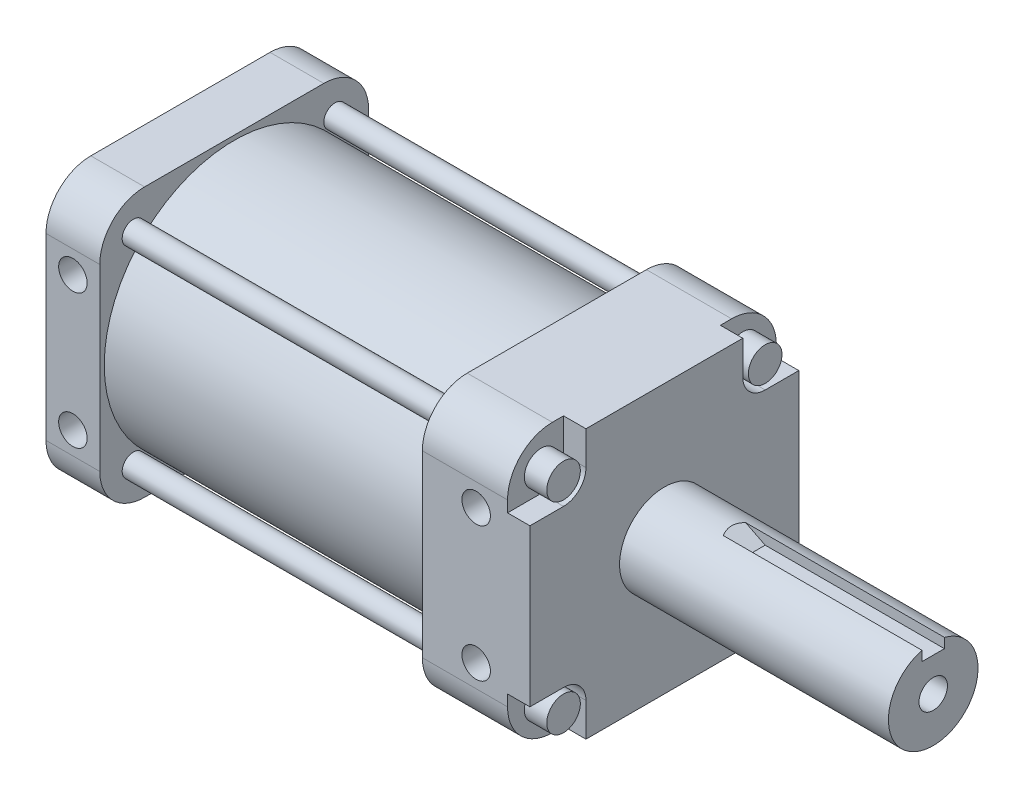
SolidWorks part; units mm, degrees
material "AISI 4130 Steel, normalized at 870C"
ref_plane "Front Plane" through (0, 0, 0) normal (0, 0, 1) x (1, 0, 0)
ref_plane "Top Plane" through (0, 0, 0) normal (0, 1, 0) x (1, 0, 0)
ref_plane "Right Plane" through (0, 0, 0) normal (1, 0, 0) x (0, 0, -1)
sketch "Sketch1" plane through (0, 0, 0) normal (1, 0, 0) x (0, 0, -1)
  line L0 (0, 19.05) -> (0, -19.05) construction
  line L1 (-12.7, 19.05) -> (12.7, 19.05)
  line L2 (-19.05, 12.7) -> (-19.05, -12.7)
  line L3 (-12.7, -19.05) -> (12.7, -19.05)
  line L4 (19.05, 12.7) -> (19.05, -12.7)
  arc A0 (12.7, 19.05) -> (19.05, 12.7) centre (12.7, 12.7) cw
  arc A1 (12.7, -19.05) -> (19.05, -12.7) centre (12.7, -12.7) ccw
  arc A2 (-19.05, -12.7) -> (-12.7, -19.05) centre (-12.7, -12.7) ccw
  arc A3 (-12.7, 19.05) -> (-19.05, 12.7) centre (-12.7, 12.7) ccw
  dimension "D2" = 6.35
  dimension "D1" = 38.1
extrude "Boss-Extrude1" add sketch "Sketch1" along normal blind 7.62
sketch "Sketch2" plane through (7.62, 0, 0) normal (1, 0, 0) x (0, 0, -1)
  circle A0 centre (0, 0) radius 18.415
  dimension "D1" = 36.83
extrude "Boss-Extrude2" add sketch "Sketch2" along normal blind 45.72
sketch "Sketch4" plane through (53.34, 0, 0) normal (1, 0, 0) x (0, 0, -1)
  line L0 (12.7, 19.05) -> (-12.7, 19.05) construction
  line L1 (-19.05, 12.7) -> (-19.05, -12.7) construction
  line L2 (-12.7, -19.05) -> (12.7, -19.05) construction
  line L3 (19.05, -12.7) -> (19.05, 12.7) construction
  line L4 (12.7, 19.05) -> (-12.7, 19.05)
  line L5 (-19.05, 12.7) -> (-19.05, -12.7)
  line L6 (-12.7, -19.05) -> (12.7, -19.05)
  line L7 (19.05, -12.7) -> (19.05, 12.7)
  arc A0 (-12.7, 19.05) -> (-19.05, 12.7) centre (-12.7, 12.7) ccw construction
  arc A1 (-19.05, -12.7) -> (-12.7, -19.05) centre (-12.7, -12.7) ccw construction
  arc A2 (12.7, -19.05) -> (19.05, -12.7) centre (12.7, -12.7) ccw construction
  arc A3 (19.05, 12.7) -> (12.7, 19.05) centre (12.7, 12.7) ccw construction
  arc A4 (-12.7, 19.05) -> (-19.05, 12.7) centre (-12.7, 12.7) ccw
  arc A5 (-19.05, -12.7) -> (-12.7, -19.05) centre (-12.7, -12.7) ccw
  arc A6 (12.7, -19.05) -> (19.05, -12.7) centre (12.7, -12.7) ccw
  arc A7 (19.05, 12.7) -> (12.7, 19.05) centre (12.7, 12.7) ccw
extrude "Boss-Extrude3" add sketch "Sketch4" along normal blind 15.24
sketch "Sketch5" plane through (68.58, 0, 0) normal (1, 0, 0) x (0, 0, -1)
  circle A0 centre (0, 0) radius 6.35
  dimension "D1" = 12.7
extrude "Boss-Extrude4" add sketch "Sketch5" along normal blind 38.1
hole_wizard "#10-32 Tapped Hole1" positions "3DSketch1" profile "Sketch6" tap size "#10-32" standard "ANSI Inch"
sketch3d "3DSketch1"
  line L18 (68.58, 0, -19.05) -> (53.34, 0, -19.05) construction
  line L19 (68.58, -12.7, -19.05) -> (68.58, 12.7, -19.05) construction
  line L20 (53.34, -12.7, -19.05) -> (53.34, 12.7, -19.05) construction
  line L23 (7.62, 0, -19.05) -> (0, 0, -19.05) construction
  line L24 (7.62, -12.7, -19.05) -> (7.62, 12.7, -19.05) construction
  line L25 (0, -12.7, -19.05) -> (0, 12.7, -19.05) construction
  line L28 (3.81, 9.525, -19.05) -> (3.81, 0, -19.05) construction
  line L31 (3.81, -9.525, -19.05) -> (3.81, 0, -19.05) construction
  line L34 (60.96, 9.525, -19.05) -> (60.96, 0, -19.05) construction
  line L35 (60.96, 0, -19.05) -> (60.96, -9.525, -19.05) construction
  point P35 (60.96, 9.525, -19.05)
  point P39 (60.96, -9.525, -19.05)
  point P41 (3.81, 9.525, -19.05)
  point P43 (3.81, -9.525, -19.05)
  point P45 (60.96, 9.525, 19.05)
  point P47 (60.96, -9.525, 19.05)
  point P49 (3.81, 9.525, 19.05)
  point P51 (3.81, -9.525, 19.05)
  dimension "D1" = 9.525
sketch "Sketch6" plane through (60.96, 9.525, -19.05) normal (1, 0, 0) x (0, 1, 0)
  line L0 (0, 0) -> (0, 8.8333)
  line L1 (0, 8.8333) -> (2.0193, 7.62)
  line L2 (2.0193, 7.62) -> (2.0193, 0)
  line L5 (2.0193, 0) -> (0, 0)
  line L10 (0, 8.8333) -> (-2.0193, 7.62) construction
  line L11 (0, -6.35) -> (0, 107.95) construction
  dimension "Tap Drill Dia." = 4.0386
  dimension "Tap Drill Depth" = 7.62
  dimension "Drill Angle" = 118
sketch "Sketch8" plane through (0, 0, 0) normal (-1, 0, 0) x (0, 0, 1)
  circle A0 centre (0, 0) radius 17.78
  dimension "D1" = 35.56
extrude "Cut-Extrude1" cut sketch "Sketch8" against normal blind 45.72 from offset 7.62 offset against normal yes
sketch "Sketch9" plane through (0, 0, 0) normal (-1, 0, 0) x (0, 0, 1)
  circle A0 centre (0, 0) radius 6
  dimension "D1" = 12
extrude "Cut-Extrude2" cut sketch "Sketch9" against normal up to next
sketch "Sketch10" plane through (0, 0, 0) normal (0, 0, 1) x (1, 0, 0)
  line L0 (106.68, 4.7625) -> (81.28, 4.7625)
  line L1 (106.68, -6.35) -> (106.68, 6.35) construction
  line L2 (81.28, 4.7625) -> (78.105, 6.35)
  line L3 (106.68, 6.35) -> (68.58, 6.35) construction
  line L4 (78.105, 6.35) -> (106.68, 6.35)
  line L5 (106.68, 6.35) -> (106.68, 4.7625)
  dimension "D1" = 1.5875
  dimension "D2" = 3.175
  dimension "D3" = 25.4
extrude "Cut-Extrude3" cut sketch "Sketch10" against normal mid plane 3.175
hole_wizard "#10-32 Tapped Hole2" positions "Sketch12" profile "Sketch11" tap size "#10-32" standard "ANSI Inch"
sketch "Sketch12" plane through (106.68, 0, 0) normal (1, 0, 0) x (0, 0, -1)
  point P0 (0, 0)
sketch "Sketch11" plane through (106.68, 0, 0) normal (0, 1, 0) x (0, 0, -1)
  line L0 (0, 0) -> (0, 8.8333)
  line L1 (0, 8.8333) -> (2.0193, 7.62)
  line L2 (2.0193, 7.62) -> (2.0193, 0)
  line L5 (2.0193, 0) -> (0, 0)
  line L10 (0, 8.8333) -> (-2.0193, 7.62) construction
  line L11 (0, -6.35) -> (0, 107.95) construction
  dimension "Tap Drill Dia." = 4.0386
  dimension "Tap Drill Depth" = 7.62
  dimension "Drill Angle" = 118
sketch "Sketch14" plane through (68.58, 0, 0) normal (1, 0, 0) x (0, 0, -1)
  line L0 (-14.2875, 11.1125) -> (-19.05, 11.1125)
  line L1 (-19.05, 12.7) -> (-19.05, -12.7) construction
  line L2 (-11.1125, 14.2875) -> (-11.1125, 19.05)
  line L3 (12.7, 19.05) -> (-12.7, 19.05) construction
  line L4 (-14.2875, -11.1125) -> (-19.05, -11.1125)
  line L5 (-11.1125, -14.2875) -> (-11.1125, -19.05)
  line L6 (-12.7, -19.05) -> (12.7, -19.05) construction
  line L7 (11.1125, 14.2875) -> (11.1125, 19.05)
  line L8 (14.2875, 11.1125) -> (19.05, 11.1125)
  line L9 (19.05, -12.7) -> (19.05, 12.7) construction
  line L10 (14.2875, -11.1125) -> (19.05, -11.1125)
  line L11 (11.1125, -14.2875) -> (11.1125, -19.05)
  line L12 (-19.05, 11.1125) -> (-19.05, 19.05)
  line L13 (-19.05, 19.05) -> (-11.1125, 19.05)
  line L14 (11.1125, 19.05) -> (19.05, 19.05)
  line L15 (19.05, 19.05) -> (19.05, 11.1125)
  line L16 (19.05, -11.1125) -> (19.05, -19.05)
  line L17 (19.05, -19.05) -> (11.1125, -19.05)
  line L18 (-11.1125, -19.05) -> (-19.05, -19.05)
  line L19 (-19.05, -19.05) -> (-19.05, -11.1125)
  arc A0 (-14.2875, 11.1125) -> (-11.1125, 14.2875) centre (-14.2875, 14.2875) ccw
  arc A1 (11.1125, 14.2875) -> (14.2875, 11.1125) centre (14.2875, 14.2875) ccw
  arc A2 (14.2875, -11.1125) -> (11.1125, -14.2875) centre (14.2875, -14.2875) ccw
  arc A3 (-11.1125, -14.2875) -> (-14.2875, -11.1125) centre (-14.2875, -14.2875) ccw
  dimension "D2" = 3.175
  dimension "D1" = 7.9375
extrude "Cut-Extrude4" cut sketch "Sketch14" against normal blind 3.175
sketch "Sketch15" plane through (53.34, 0, 0) normal (-1, 0, 0) x (0, 0, 1)
  circle A0 centre (14.2875, 14.2875) radius 1.5875
  circle A1 centre (-14.2875, 14.2875) radius 1.5875
  circle A2 centre (14.2875, -14.2875) radius 1.5875
  circle A3 centre (-14.2875, -14.2875) radius 1.5875
  dimension "D1" = 3.175
extrude "Boss-Extrude5" add sketch "Sketch15" along normal up to next
sketch "Sketch16" plane through (65.405, 0, 0) normal (1, 0, 0) x (0, 0, -1)
  circle A0 centre (-14.2875, 14.2875) radius 2.3813
  circle A1 centre (-14.2875, -14.2875) radius 2.3813
  circle A2 centre (14.2875, -14.2875) radius 2.3813
  circle A3 centre (14.2875, 14.2875) radius 2.3813
  dimension "D1" = 4.7625
extrude "Boss-Extrude6" add sketch "Sketch16" along normal blind 3.175
